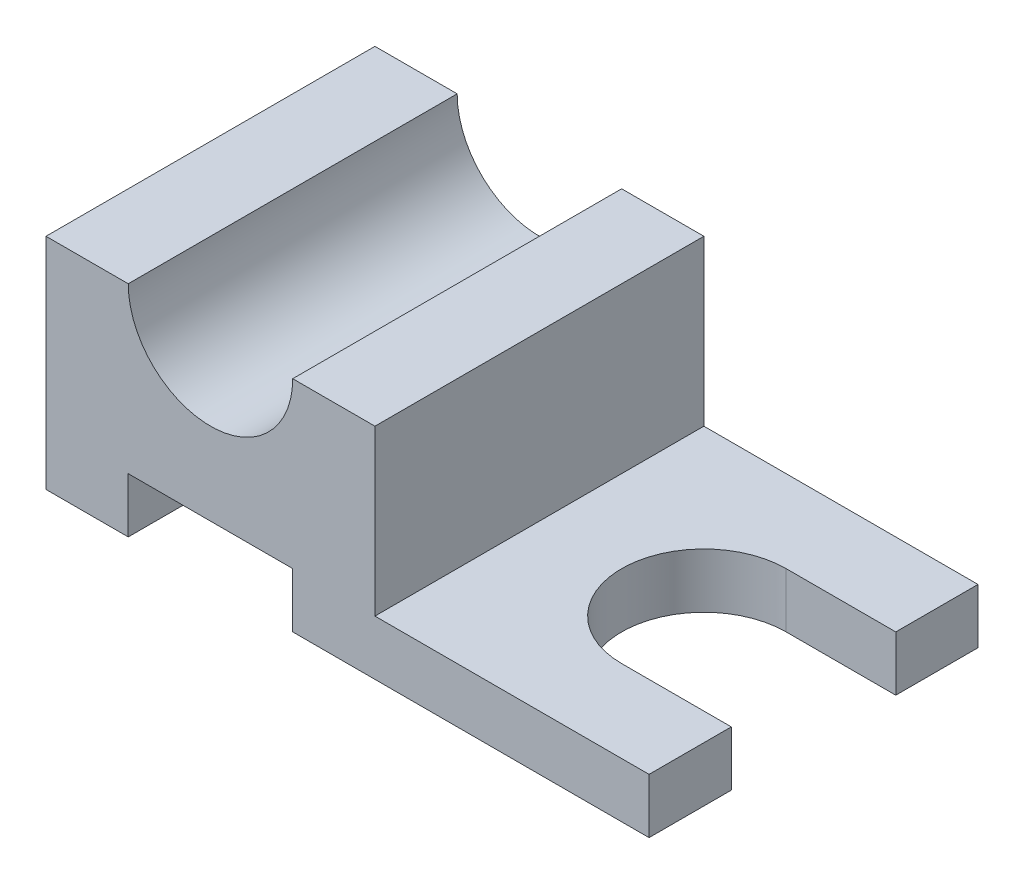
SolidWorks part; units mm, degrees
ref_plane "Front Plane" through (0, 0, 0) normal (0, 0, 1) x (1, 0, 0)
ref_plane "Top Plane" through (0, 0, 0) normal (0, 1, 0) x (1, 0, 0)
ref_plane "Right Plane" through (0, 0, 0) normal (1, 0, 0) x (0, 0, -1)
sketch "Sketch1" plane through (0, 0, 0) normal (0, 0, 1) x (1, 0, 0)
  line L0 (-114.1745, -58.7242) -> (-99.1745, -58.7242)
  line L1 (-114.1745, -58.7242) -> (-114.1745, -18.7242)
  line L2 (-114.1745, -18.7242) -> (-99.1745, -18.7242)
  line L4 (-69.1745, -18.7242) -> (-54.1745, -18.7242)
  line L5 (-54.1745, -18.7242) -> (-54.1745, -48.7242)
  line L6 (-4.1745, -58.7242) -> (-4.1745, -48.7242)
  line L7 (-4.1745, -48.7242) -> (-54.1745, -48.7242)
  line L8 (-99.1745, -48.7242) -> (-99.1745, -58.7242)
  line L9 (-69.1745, -48.7242) -> (-69.1745, -58.7242)
  line L10 (-99.1745, -58.7242) -> (-99.1745, -48.7242)
  line L11 (-99.1745, -48.7242) -> (-69.1745, -48.7242)
  line L12 (-69.1745, -58.7242) -> (-4.1745, -58.7242)
  arc A0 (-99.1745, -18.7242) -> (-69.1745, -18.7242) centre (-84.1745, -18.7242) ccw
extrude "Boss-Extrude1" add sketch "Sketch1" along normal blind 60 contours A0 L2 L1 L0 L8 L11 L9 L12 L6 L7 L5 L4
sketch "Sketch2" plane through (0, -48.7242, 0) normal (0, 1, 0) x (1, 0, 0)
  line L0 (-4.1745, -15) -> (-4.1745, -45)
  line L4 (-24.1745, -15) -> (-4.1745, -15)
  line L5 (-4.1745, -60) -> (-4.1745, 0) construction
  line L6 (-24.1745, -45) -> (-4.1745, -45)
  arc A0 (-24.1745, -15) -> (-24.1745, -45) centre (-24.1745, -30) ccw
extrude "Cut-Extrude1" cut sketch "Sketch2" against normal blind 10
